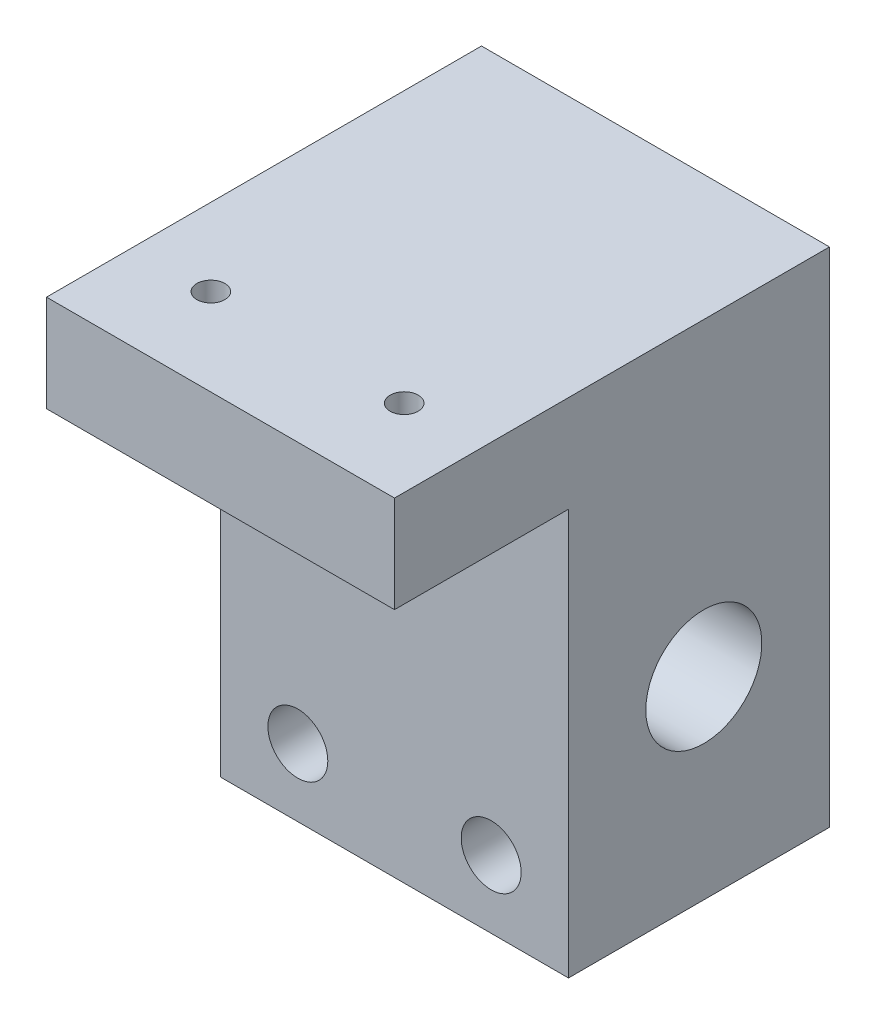
SolidWorks part; units mm, degrees
ref_plane "前视基准面" through (0, 0, 0) normal (0, 0, 1) x (1, 0, 0)
ref_plane "上视基准面" through (0, 0, 0) normal (0, 1, 0) x (1, 0, 0)
ref_plane "右视基准面" through (0, 0, 0) normal (1, 0, 0) x (0, 0, -1)
other "Configuration Table"
sketch "草图1" plane through (0, 0, 0) normal (0, 1, 0) x (1, 0, 0)
  line L1 (0, 0) -> (36, 0)
  line L2 (0, 0) -> (0, 24)
  line L3 (0, 24) -> (36, 24)
  line L4 (36, 0) -> (36, 24)
  dimension "D1" = 36
  dimension "D2" = 24
extrude "凸台-拉伸1" add sketch "草图1" along normal blind 55
sketch "草图2" plane through (0, 0, 0) normal (-1, 0, 0) x (0, 0, 1)
  line L0 (-24, 0) -> (0, 0) construction
  line L1 (-24, 55) -> (-24, 0) construction
  circle A0 centre (-14, 23) radius 6
  dimension "D1" = 23
  dimension "D2" = 12
  dimension "D3" = 10
extrude "切除-拉伸1" cut sketch "草图2" against normal up to surface (36 mm away) up to face at (36, 27.5, -12)
sketch "草图3" plane through (0, 0, 0) normal (0, 0, 1) x (1, 0, 0)
  line L0 (0, 0) -> (36, 0) construction
  line L1 (0, 55) -> (0, 0) construction
  circle A0 centre (8, 10) radius 3.1
  circle A1 centre (28, 10) radius 3.1
  dimension "D1" = 6.2
  dimension "D2" = 6.2
  dimension "D3" = 10
  dimension "D4" = 20
  dimension "D5" = 8
extrude "切除-拉伸2" cut sketch "草图3" against normal blind 6
sketch "草图5" plane through (36, 0, 0) normal (1, 0, 0) x (0, 0, -1)
  line L0 (0, 55) -> (24, 55) construction
  line L1 (0, 55) -> (0, 0) construction
  line L2 (0, 55) -> (-18, 55)
  line L3 (0, 55) -> (0, 45)
  line L4 (0, 45) -> (-18, 45)
  line L5 (-18, 55) -> (-18, 45)
  dimension "D1" = 18
  dimension "D2" = 10
extrude "凸台-拉伸2" add sketch "草图5" against normal up to surface (36 mm away) up to face at (0, 23, -8)
sketch "草图6" plane through (0, 55, 0) normal (0, 1, 0) x (1, 0, 0)
  line L0 (0, 24) -> (0, -18) construction
  line L1 (36, 24) -> (0, 24) construction
  circle A0 centre (28, -9) radius 1.45
  circle A1 centre (8, -9) radius 1.45
  dimension "D1" = 2.9
  dimension "D2" = 2.9
  dimension "D3" = 20
  dimension "D4" = 8
  dimension "D5" = 33
extrude "切除-拉伸3" cut sketch "草图6" against normal blind 5
sketch "草图7" plane through (0, 0, -24) normal (0, 0, -1) x (-1, 0, 0)
  line L4 (-36, 0) -> (0, 0)
  line L5 (0, 0) -> (0, 55)
  line L6 (0, 55) -> (-36, 55)
  line L7 (-36, 55) -> (-36, 0)
  line L8 (-36, 0) -> (0, 0)
  line L9 (0, 0) -> (0, 55)
  line L10 (0, 55) -> (-36, 55)
  line L11 (-36, 55) -> (-36, 0)
  dimension "D1" = 0
extrude "凸台-拉伸3" add sketch "草图7" along normal blind 3
sketch "草图8" plane through (0, 0, 0) normal (0, -1, 0) x (1, 0, 0)
  line L4 (0, 0) -> (0, -27)
  line L5 (0, -27) -> (36, -27)
  line L6 (36, -27) -> (36, 0)
  line L7 (36, 0) -> (0, 0)
  line L8 (0, 0) -> (0, -27)
  line L9 (0, -27) -> (36, -27)
  line L10 (36, -27) -> (36, 0)
  line L11 (36, 0) -> (0, 0)
  dimension "D1" = 0
extrude "切除-拉伸4" cut sketch "草图8" against normal blind 3
sketch "草图9" plane through (0, 50, 0) normal (0, 1, 0) x (1, 0, 0)
  circle A1 centre (8, -9) radius 1.45
  circle A2 centre (8, -9) radius 1.45
  dimension "D1" = 0
extrude "切除-拉伸5" cut sketch "草图9" against normal blind 1.5
